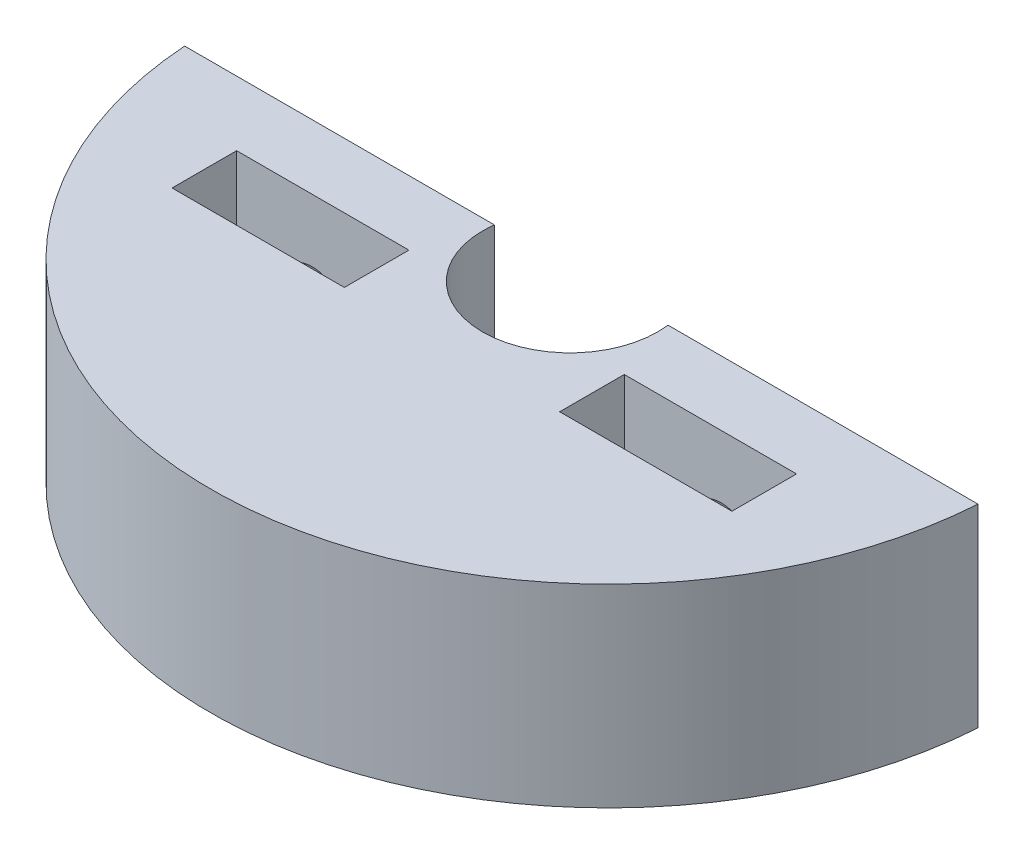
SolidWorks part; units mm, degrees
ref_plane "Alzado" through (0, 0, 0) normal (0, 0, 1) x (1, 0, 0)
ref_plane "Planta" through (0, 0, 0) normal (0, 1, 0) x (1, 0, 0)
ref_plane "Vista lateral" through (0, 0, 0) normal (1, 0, 0) x (0, 0, -1)
sketch "Sketch1" plane through (0, 0, 0) normal (0, 1, 0) x (1, 0, 0)
  line L0 (25.3345, 26.2686) -> (39.7185, 26.2686)
  line L5 (47.781, 26.2686) -> (62.1767, 26.2686)
  line L6 (28.3556, 27.2686) -> (59.1556, 27.2686) construction
  line L7 (39.8554, 26.3806) -> (39.7185, 26.2686) construction
  line L8 (47.636, 26.2979) -> (47.781, 26.2686) construction
  circle A0 centre (43.7556, 27.2686) radius 19 construction
  arc A1 (25.3345, 26.2686) -> (62.1767, 26.2686) centre (43.7556, 27.5186) ccw
  arc A4 (39.7185, 26.2686) -> (47.781, 26.2686) centre (43.7498, 25.7518) ccw
  arc A6 (47.7556, 27.2686) -> (39.7556, 27.2686) centre (43.7556, 27.2686) ccw construction
  point P10 (47.7257, 24.2699)
  dimension "D1" = 1
  dimension "D4" = 0.25
  dimension "D2" = 1
extrude "Boss-Extrude1" add sketch "Sketch1" along normal blind 9
ref_plane "Plane1" through (43.7556, 0.002, -52.2686) normal (0, 0, 1) x (1, 0, 0)
sketch "Sketch2" plane through (43.7556, 0.002, -52.2686) normal (0, 0, 1) x (1, 0, 0)
  line L0 (-18.4211, -0.002) -> (18.4211, -0.002) construction
  line L1 (-4.0371, 8.998) -> (-4.0371, -0.002) construction
  line L3 (4.0254, 8.998) -> (4.0254, -0.002) construction
  circle A0 centre (9.5, 4.5) radius 1.585
  circle A2 centre (-9.5, 4.5) radius 1.585
  dimension "D3" = 3.17
  dimension "D4" = 3.17
  dimension "D1" = 4.502
  dimension "D2" = 4.502
  dimension "D5" = 5.4746
  dimension "D6" = 5.4629
extrude "Cut-Extrude1" cut sketch "Sketch2" along normal blind 32
sketch "Sketch3" plane through (0, 9, 0) normal (0, 1, 0) x (1, 0, 0)
  line L0 (62.1767, 26.2686) -> (47.781, 26.2686) construction
  line L1 (48.7498, 23.2686) -> (56.7498, 23.2686)
  line L2 (48.7498, 23.2686) -> (48.7498, 20.2686)
  line L3 (48.7498, 20.2686) -> (56.7498, 20.2686)
  line L4 (56.7498, 23.2686) -> (56.7498, 20.2686)
  line L5 (39.7185, 26.2686) -> (25.3345, 26.2686) construction
  line L6 (38.7498, 23.2686) -> (30.7498, 23.2686)
  line L7 (38.7498, 23.2686) -> (38.7498, 20.2686)
  line L8 (38.7498, 20.2686) -> (30.7498, 20.2686)
  line L9 (30.7498, 23.2686) -> (30.7498, 20.2686)
  arc A0 (39.7185, 26.2686) -> (47.781, 26.2686) centre (43.7498, 25.7518) ccw construction
  dimension "D1" = 8
  dimension "D2" = 3
  dimension "D3" = 3
  dimension "D4" = 8
  dimension "D5" = 5
  dimension "D6" = 5
  dimension "D7" = 3
  dimension "D8" = 3
extrude "Cut-Extrude4" cut sketch "Sketch3" against normal blind 32
